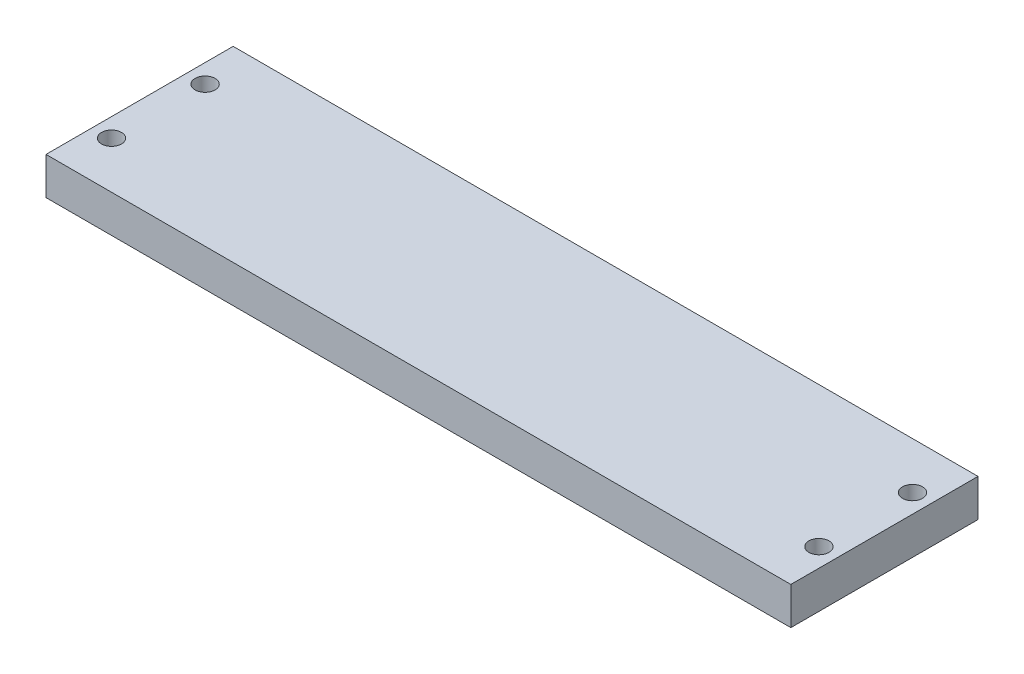
SolidWorks part; units mm, degrees
ref_plane "Front Plane" through (0, 0, 0) normal (0, 0, 1) x (1, 0, 0)
ref_plane "Top Plane" through (0, 0, 0) normal (0, 1, 0) x (1, 0, 0)
ref_plane "Right Plane" through (0, 0, 0) normal (1, 0, 0) x (0, 0, -1)
sketch "Sketch2" plane through (0, 0, 0) normal (0, 1, 0) x (1, 0, 0)
  line L1 (-132.164, -185.5749) -> (120.536, -185.5749)
  line L2 (-132.164, -185.5749) -> (-132.164, -249.0749)
  line L3 (-132.164, -249.0749) -> (120.536, -249.0749)
  line L4 (120.536, -185.5749) -> (120.536, -249.0749)
  point P6 (-125.814, -201.4499)
  point P7 (-125.814, -233.1999)
  point P9 (114.186, -201.4499)
  point P11 (114.186, -233.1999)
extrude "Boss-Extrude2" add sketch "Sketch2" along normal blind 12.7
sketch "Sketch3" plane through (0, 12.7, 0) normal (0, 1, 0) x (1, 0, 0)
  line L6 (-5.814, -185.5749) -> (-5.814, -249.0749) construction
  line L7 (120.536, -185.5749) -> (-132.164, -185.5749) construction
  line L8 (-132.164, -249.0749) -> (120.536, -249.0749) construction
  line L9 (-132.164, -217.3249) -> (120.536, -217.3249) construction
  line L10 (-132.164, -185.5749) -> (-132.164, -249.0749) construction
  line L11 (120.536, -249.0749) -> (120.536, -185.5749) construction
  point P23 (-125.814, -201.4499)
  point P24 (-125.814, -233.1999)
  point P25 (114.186, -233.1999)
  point P26 (114.186, -201.4499)
hole_wizard "Tap Drill for M8x1.25 Tap1" positions "3DSketch1" profile "Sketch6" hole size "M8x1.25" standard "Ansi Metric"
sketch3d "3DSketch1"
  point P0 (-125.814, 12.7, 201.4499)
  point P4 (-125.814, 12.7, 233.1999)
  point P7 (114.186, 12.7, 201.4499)
  point P10 (114.186, 12.7, 233.1999)
sketch "Sketch6" plane through (-125.814, 12.7, 201.4499) normal (1, 0, 0) x (0, 0, 1)
  line L0 (0, 0) -> (0, 42.0429)
  line L1 (0, 42.0429) -> (3.4, 40)
  line L2 (3.4, 40) -> (3.4, 0)
  line L5 (3.4, 0) -> (0, 0)
  line L10 (0, 42.0429) -> (-3.4, 40) construction
  line L11 (0, -6.35) -> (0, 107.95) construction
  dimension "Hole Dia." = 6.8
  dimension "Hole Depth" = 40
  dimension "Drill Angle" = 118
